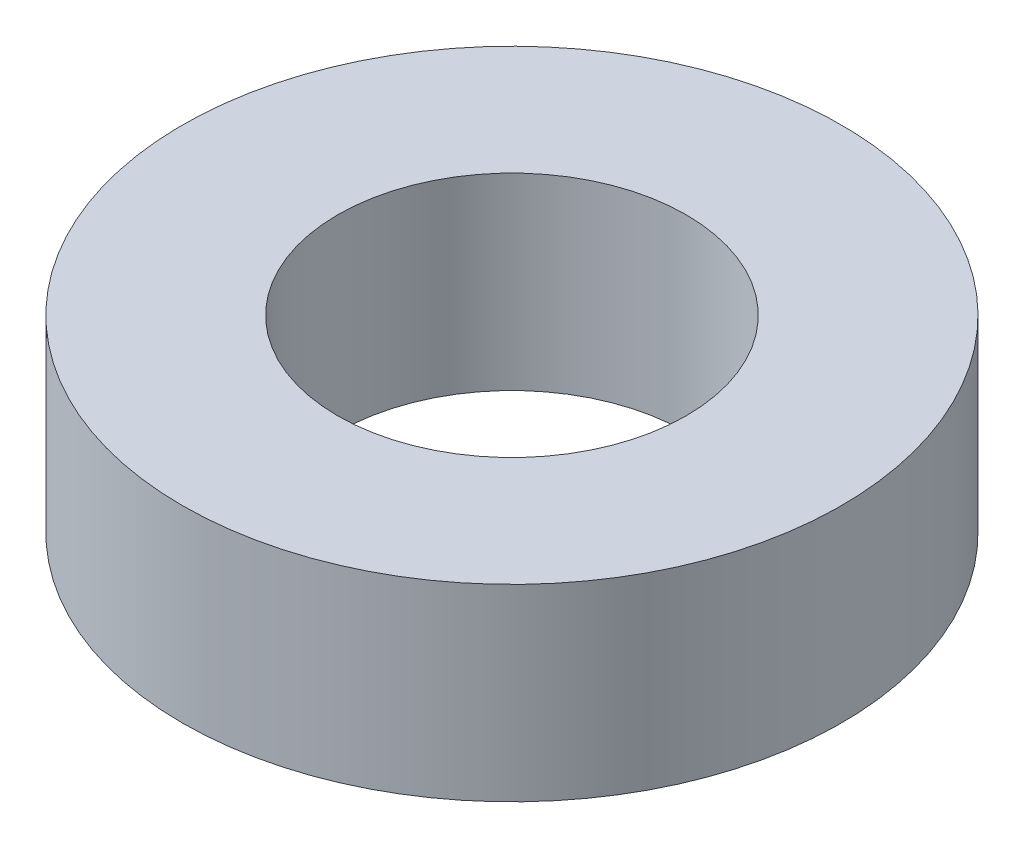
SolidWorks part; units mm, degrees
material "201 退火不锈钢 (SS)"
ref_plane "前视基准面" through (0, 0, 0) normal (0, 0, 1) x (1, 0, 0)
ref_plane "上视基准面" through (0, 0, 0) normal (0, 1, 0) x (1, 0, 0)
ref_plane "右视基准面" through (0, 0, 0) normal (1, 0, 0) x (0, 0, -1)
sketch "草图1" plane through (0, 0, 0) normal (0, 1, 0) x (1, 0, 0)
  circle A0 centre (0, 0) radius 1.85
  circle A1 centre (0, 0) radius 3.5
  dimension "D1" = 3.7
  dimension "D2" = 7
extrude "凸台-拉伸1" add sketch "草图1" along normal blind 2
